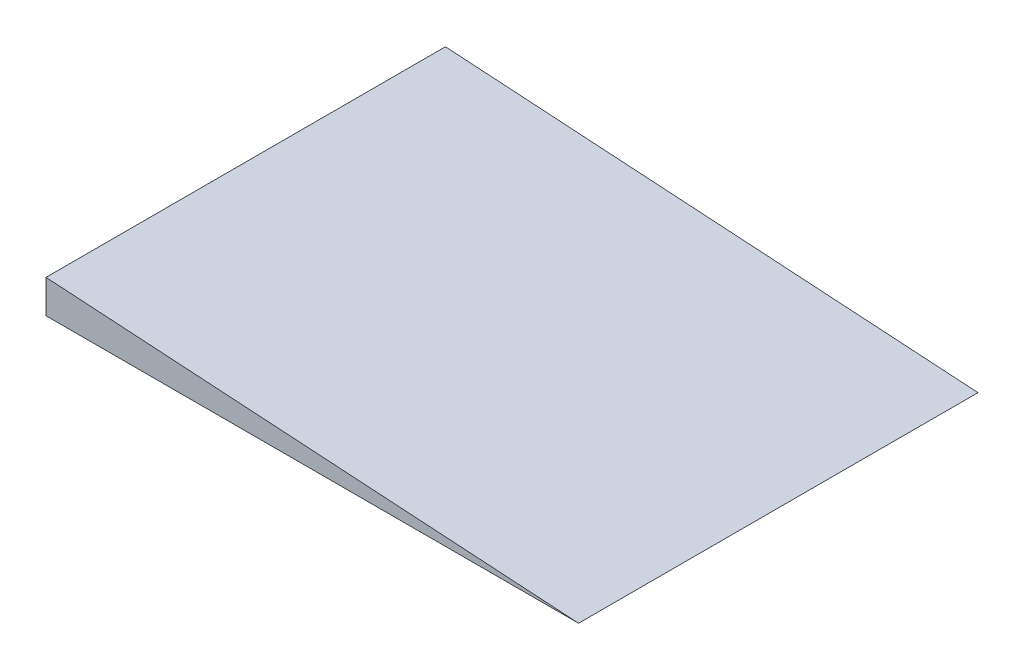
SolidWorks part; units mm, degrees
ref_plane "Front Plane" through (0, 0, 0) normal (0, 0, 1) x (1, 0, 0)
ref_plane "Top Plane" through (0, 0, 0) normal (0, 1, 0) x (1, 0, 0)
ref_plane "Right Plane" through (0, 0, 0) normal (1, 0, 0) x (0, 0, -1)
sketch "Sketch1" plane through (0, 0, 0) normal (0, 0, 1) x (1, 0, 0)
  line L0 (0, 0) -> (203.2, 0)
  line L1 (203.2, 0) -> (0, 12.7)
  line L2 (0, 12.7) -> (0, 0)
  dimension "D1" = 12.7
  dimension "D2" = 203.2
extrude "Boss-Extrude1" add sketch "Sketch1" along normal blind 152.4
